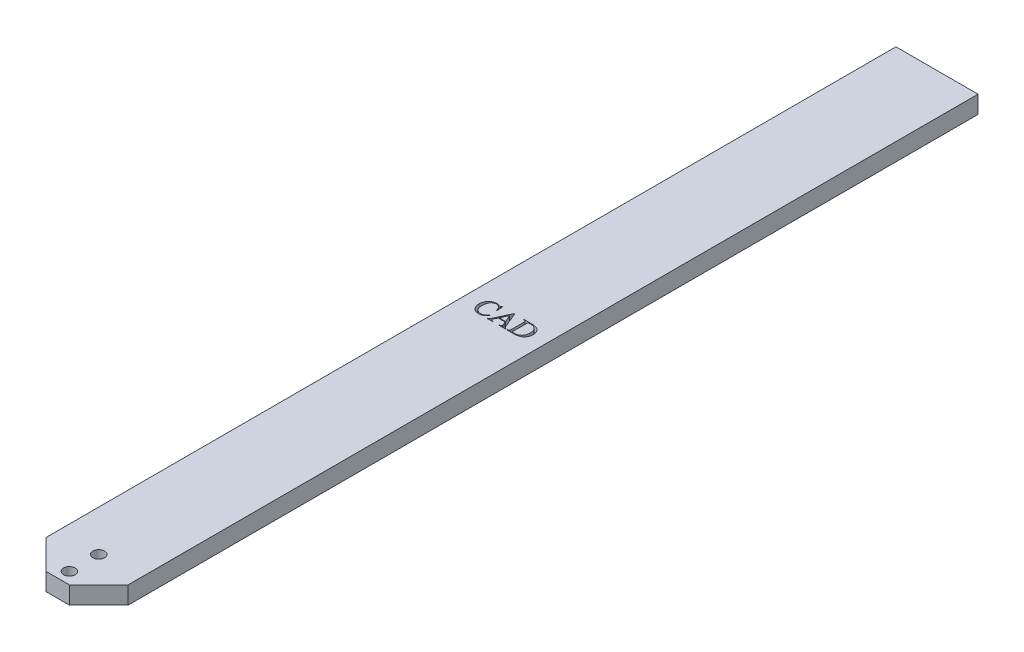
SolidWorks part; units mm, degrees
material "Acrylic (Medium-high impact)"
ref_plane "Front Plane" through (0, 0, 0) normal (0, 0, 1) x (1, 0, 0)
ref_plane "Top Plane" through (0, 0, 0) normal (0, 1, 0) x (1, 0, 0)
ref_plane "Right Plane" through (0, 0, 0) normal (1, 0, 0) x (0, 0, -1)
sketch "Sketch2" plane through (0, 0, 0) normal (0, 0, 1) x (1, 0, 0)
  line L1 (-7, 1.5) -> (7, 1.5)
  line L2 (-7, 1.5) -> (-7, -1.5)
  line L3 (-7, -1.5) -> (7, -1.5)
  line L4 (7, 1.5) -> (7, -1.5)
  line L5 (-7, 1.5) -> (7, -1.5) construction
  line L6 (-7, -1.5) -> (7, 1.5) construction
  point P0 (0, 0)
  dimension "D1" = 14
  dimension "D2" = 3
extrude "Boss-Extrude1" add sketch "Sketch2" along normal blind 150
sketch "Sketch3" plane through (0, 1.5, 0) normal (0, 1, 0) x (1, 0, 0)
  line L0 (7, -150) -> (-7, -150) construction
  line L1 (-7, -150) -> (-7, 0) construction
  circle A0 centre (0, -148) radius 1
  dimension "D1" = 2
  dimension "D2" = 2
  dimension "D3" = 7
extrude "Cut-Extrude1" cut sketch "Sketch3" against normal through all
chamfer "Chamfer1" distance 5 angle 45 2 edges at (7, 0, 150) (-7, 0, 150)
sketch "Sketch4" plane through (0, 1.5, 0) normal (0, 1, 0) x (1, 0, 0)
  line L0 (-7, -75) -> (7, -75) construction
  line L1 (-7, -145) -> (-7, 0) construction
  line L2 (7, -145) -> (7, 0) construction
  line L3 (7, 0) -> (-7, 0) construction
  text T0 "CAD" font "Times New Roman" height 3
  dimension "D1" = 75
extrude "Cut-Extrude2" cut sketch "Sketch4" against normal blind 1
sketch "Sketch5" plane through (0, 1.5, 0) normal (0, 1, 0) x (1, 0, 0)
  circle A0 centre (0, -143) radius 1
  circle A1 centre (0, -148) radius 1 construction
  dimension "D1" = 2
  dimension "D2" = 5
extrude "Cut-Extrude3" cut sketch "Sketch5" against normal through all
